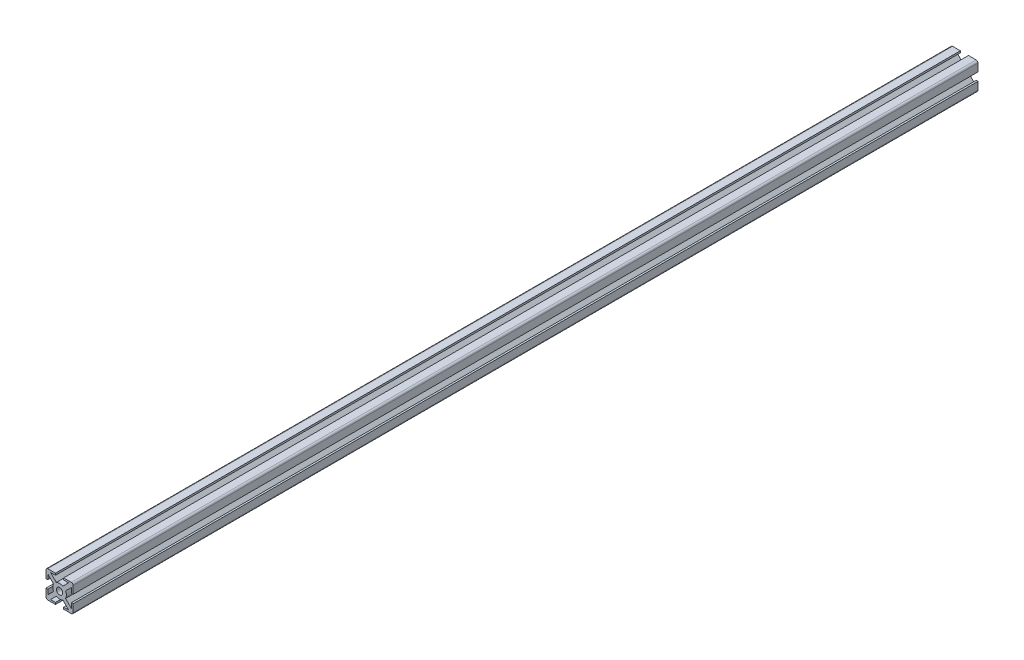
SolidWorks part; units mm, degrees
ref_plane "Plano frontal" through (0, 0, 0) normal (0, 0, 1) x (1, 0, 0)
ref_plane "Plano superior" through (0, 0, 0) normal (0, 1, 0) x (1, 0, 0)
ref_plane "Plano direito" through (0, 0, 0) normal (1, 0, 0) x (0, 0, -1)
sketch "Esboço1" plane through (0, 0, 0) normal (0, 0, 1) x (1, 0, 0)
  line L0 (-0.4095, -0.4095) -> (-30.4095, -30.4095) construction
  line L1 (-28.4095, -0.4095) -> (-19.9095, -0.4095)
  line L2 (-30.4095, -2.4095) -> (-30.4095, -10.9095)
  line L3 (-28.4095, -30.4095) -> (-19.9095, -30.4095)
  line L4 (-0.4095, -2.4095) -> (-0.4095, -10.9095)
  line L5 (-15.4095, -15.4095) -> (-15.4095, -0.4095) construction
  line L6 (-15.4095, -15.4095) -> (-0.4095, -15.4095) construction
  line L7 (-10.9095, -0.4095) -> (-2.4095, -0.4095)
  line L8 (-0.4095, -19.9095) -> (-0.4095, -28.4095)
  line L9 (-0.4095, -28.4095) -> (-0.4095, -19.9095)
  line L10 (-8.8227, -11.8227) -> (-2.4095, -5.4095)
  line L11 (-10.9095, -2.4095) -> (-5.4095, -2.4095)
  line L12 (-2.4095, -5.4095) -> (-2.4095, -10.9095)
  line L13 (-2.4095, -10.9095) -> (-0.4095, -10.9095)
  line L14 (-10.9095, -2.4095) -> (-10.9095, -0.4095)
  line L15 (-11.8227, -8.8227) -> (-5.4095, -2.4095)
  line L16 (-2.4095, -19.9095) -> (-0.4095, -19.9095)
  line L17 (-2.4095, -25.4095) -> (-2.4095, -19.9095)
  line L18 (-8.8227, -18.9962) -> (-2.4095, -25.4095)
  line L19 (-11.8227, -21.9962) -> (-5.4095, -28.4095)
  line L20 (-10.9095, -28.4095) -> (-5.4095, -28.4095)
  line L21 (-10.9095, -28.4095) -> (-10.9095, -30.4095)
  line L22 (-10.9095, -30.4095) -> (-2.4095, -30.4095)
  line L23 (-19.9095, -28.4095) -> (-19.9095, -30.4095)
  line L24 (-19.9095, -28.4095) -> (-25.4095, -28.4095)
  line L25 (-18.9962, -21.9962) -> (-25.4095, -28.4095)
  line L26 (-21.9962, -18.9962) -> (-28.4095, -25.4095)
  line L27 (-28.4095, -25.4095) -> (-28.4095, -19.9095)
  line L28 (-30.4095, -19.9095) -> (-30.4095, -28.4095)
  line L29 (-28.4095, -19.9095) -> (-30.4095, -19.9095)
  line L30 (-21.9962, -11.8227) -> (-28.4095, -5.4095)
  line L31 (-28.4095, -10.9095) -> (-30.4095, -10.9095)
  line L32 (-30.4095, -2.4095) -> (-30.4095, -10.9095)
  line L33 (-19.9095, -0.4095) -> (-28.4095, -0.4095)
  line L34 (-19.9095, -2.4095) -> (-19.9095, -0.4095)
  line L35 (-19.9095, -2.4095) -> (-25.4095, -2.4095)
  line L36 (-18.9962, -8.8227) -> (-25.4095, -2.4095)
  line L37 (-30.4095, -19.9095) -> (-30.4095, -28.4095)
  line L38 (-10.9095, -30.4095) -> (-2.4095, -30.4095)
  line L39 (-28.4095, -5.4095) -> (-28.4095, -10.9095)
  arc A0 (-11.8227, -8.8227) -> (-18.9962, -8.8227) centre (-15.4095, -15.4095) ccw
  circle A1 centre (-15.4095, -15.4095) radius 3.5
  arc A2 (-18.9962, -21.9962) -> (-11.8227, -21.9962) centre (-15.4095, -15.4095) ccw
  arc A3 (-21.9962, -11.8227) -> (-21.9962, -18.9962) centre (-15.4095, -15.4095) ccw
  arc A4 (-30.4095, -28.4095) -> (-28.4095, -30.4095) centre (-28.4095, -28.4095) ccw
  arc A5 (-2.4095, -30.4095) -> (-0.4095, -28.4095) centre (-2.4095, -28.4095) ccw
  arc A6 (-0.4095, -2.4095) -> (-2.4095, -0.4095) centre (-2.4095, -2.4095) ccw
  arc A7 (-30.4095, -2.4095) -> (-28.4095, -0.4095) centre (-28.4095, -2.4095) cw
  arc A8 (-8.8227, -18.9962) -> (-8.8227, -11.8227) centre (-15.4095, -15.4095) ccw
  dimension "D3" = 15
  dimension "D4" = 7
  dimension "D7" = 2
  dimension "D5" = 4.5
  dimension "D6" = 4.5
  dimension "D11" = 2
  dimension "D12" = 2
extrude "Ressalto-extrusão1" add sketch "Esboço1" against normal blind 1000 contours L18 A8 L10 L12 L13 L4 A6 L7 L14 L11 L15 A0 L36 L35 L34 L1 A7 L2 L31 L39 L30 A3 L26 L27 L29 L28 A4 L3 L23 L24 L25 A2 L19 L20 L21 L22 A5 L8 L16 L17 A1
